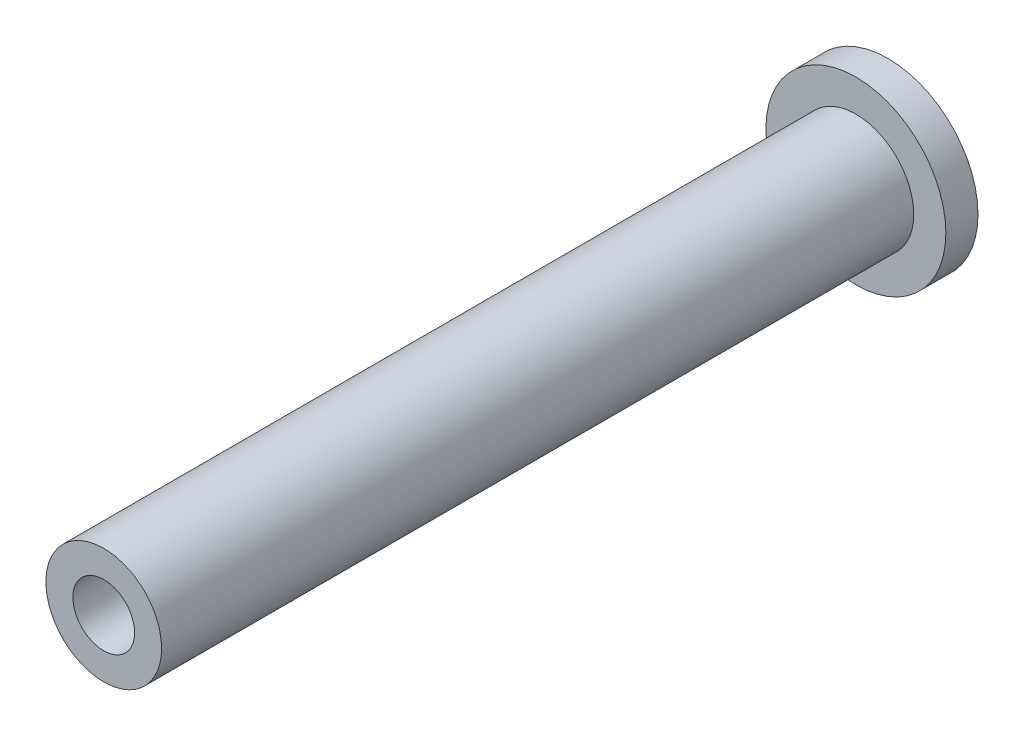
SolidWorks part; units mm, degrees
ref_plane "前视基准面" through (0, 0, 0) normal (0, 0, 1) x (1, 0, 0)
ref_plane "上视基准面" through (0, 0, 0) normal (0, 1, 0) x (1, 0, 0)
ref_plane "右视基准面" through (0, 0, 0) normal (1, 0, 0) x (0, 0, -1)
other "Configuration Table"
sketch "Sketch1" plane through (0, 0, 0) normal (0, 0, 1) x (1, 0, 0)
  circle A0 centre (0, 0) radius 7
  dimension "D1" = 14
extrude "Boss-Extrude1" add sketch "Sketch1" along normal blind 2.5
sketch "Sketch2" plane through (0, 0, 2.5) normal (0, 0, 1) x (1, 0, 0)
  circle A0 centre (0, 0) radius 4.5
  dimension "D1" = 9
extrude "Boss-Extrude2" add sketch "Sketch2" along normal blind 58.5
sketch "Sketch3" plane through (0, 0, 61) normal (0, 0, 1) x (1, 0, 0)
  circle A1 centre (0, 0) radius 2.4
  dimension "D1" = 4.8
extrude "Cut-Extrude1" cut sketch "Sketch3" against normal blind 5
